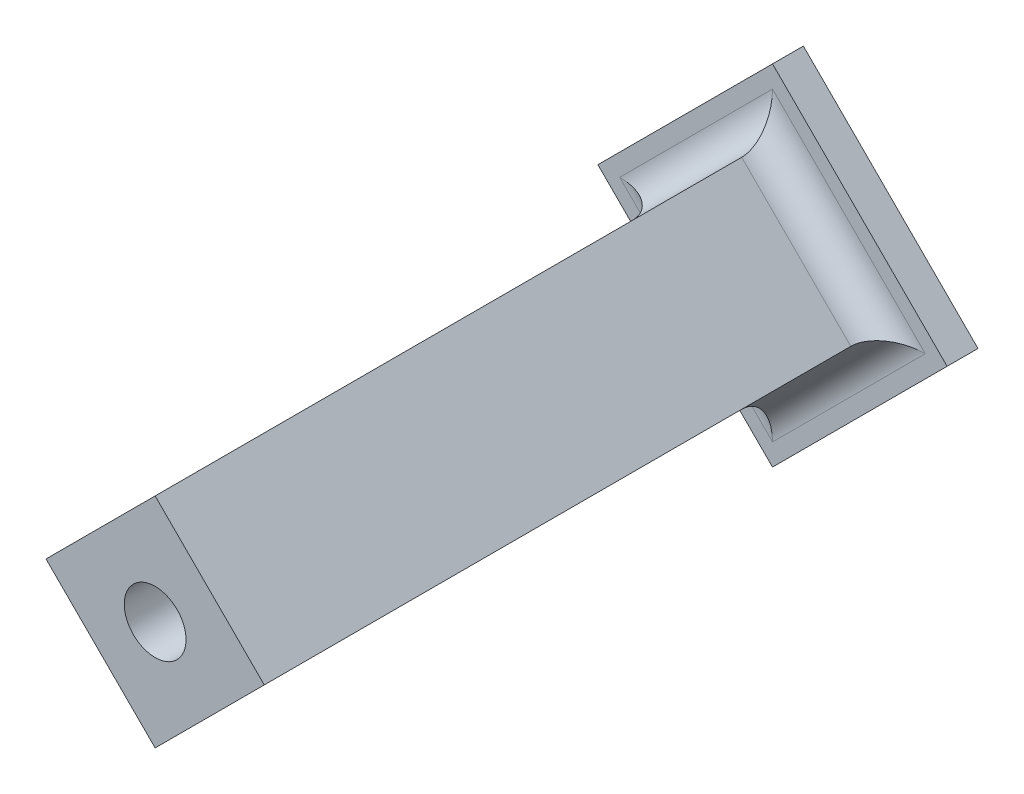
SolidWorks part; units mm, degrees
ref_plane "Front Plane" through (0, 0, 0) normal (0, 0, 1) x (1, 0, 0)
ref_plane "Top Plane" through (0, 0, 0) normal (0, 1, 0) x (1, 0, 0)
ref_plane "Right Plane" through (0, 0, 0) normal (1, 0, 0) x (0, 0, -1)
sketch "Sketch1" plane through (0, 0, 0) normal (0, 0, 1) x (1, 0, 0)
  line L0 (-5.6569, 0) -> (0, 5.6569)
  line L1 (-5.6569, 0) -> (0, -5.6569)
  line L2 (0, 5.6569) -> (5.6569, 0)
  line L3 (0, -5.6569) -> (5.6569, 0)
  line L4 (-5.6569, 0) -> (5.6569, 0) construction
  line L5 (0, 5.6569) -> (0, -5.6569) construction
  point P1 (0, 0)
  dimension "D1" = 8
extrude "Base" add sketch "Sketch1" along normal blind 1
sketch "Sketch2" plane through (0, 0, 1) normal (0, 0, 1) x (1, 0, 0)
  line L0 (0, -3.5355) -> (3.5355, 0)
  line L1 (0, -3.5355) -> (-3.5355, 0)
  line L2 (3.5355, 0) -> (0, 3.5355)
  line L3 (-3.5355, 0) -> (0, 3.5355)
  line L4 (0, -3.5355) -> (0, 3.5355) construction
  line L5 (3.5355, 0) -> (-3.5355, 0) construction
  point P1 (0, 0)
  dimension "D1" = 5
extrude "Boss-Extrude2" add sketch "Sketch2" along normal blind 20
sketch "Sketch3" plane through (0, 0, 21) normal (0, 0, 1) x (1, 0, 0)
  circle A0 centre (0, 0) radius 1
  dimension "D1" = 2
extrude "Cut-Extrude1" cut sketch "Sketch3" against normal through all
fillet "Fillet1" radius 1 4 edges at (1.7678, 1.7678, 1) (1.7678, -1.7678, 1) (-1.7678, -1.7678, 1) (-1.7678, 1.7678, 1)
sketch "Sketch4" plane through (0, 0, 0) normal (0, 0, -1) x (-1, 0, 0)
  circle A0 centre (0, 0) radius 3
  dimension "D1" = 6
extrude "Cut-Extrude2" cut sketch "Sketch4" against normal blind 1
